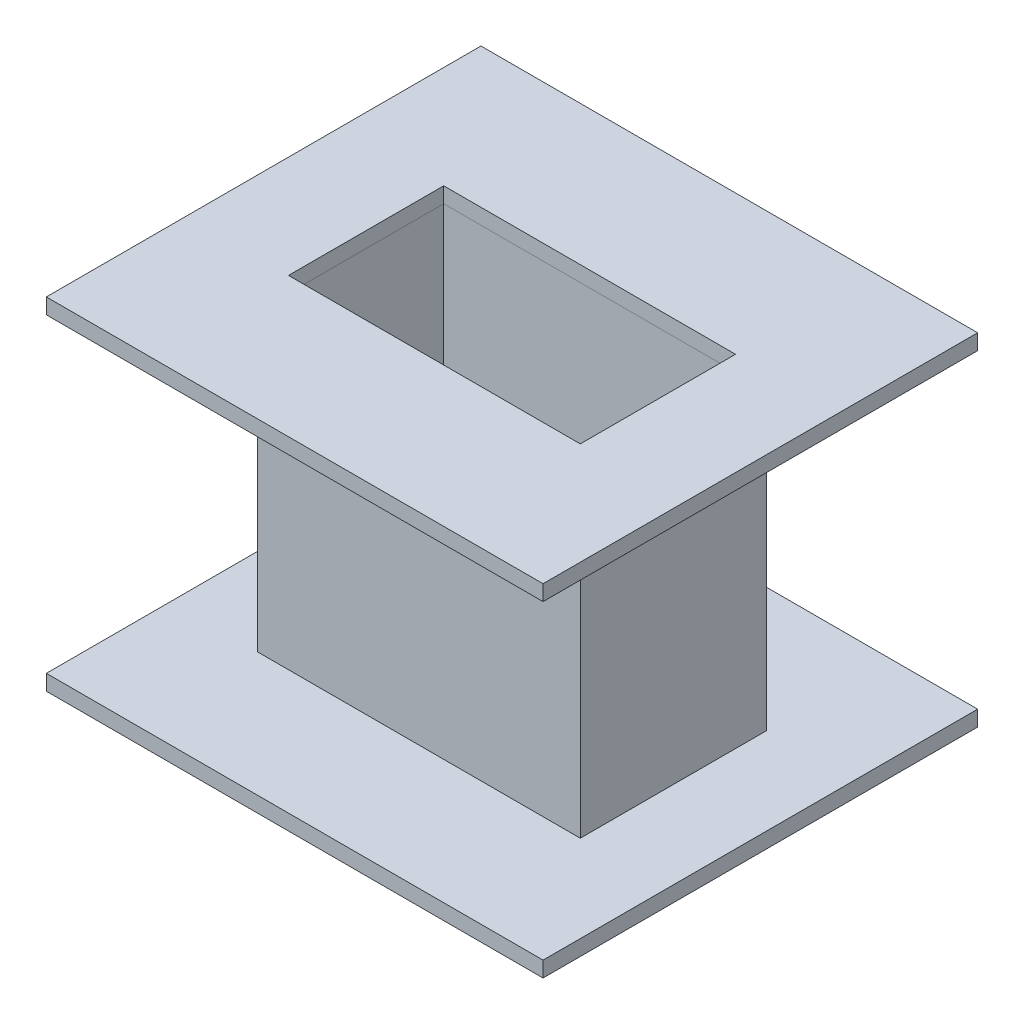
SolidWorks part; units mm, degrees
ref_plane "Front Plane" through (0, 0, 0) normal (0, 0, 1) x (1, 0, 0)
ref_plane "Top Plane" through (0, 0, 0) normal (0, 1, 0) x (1, 0, 0)
ref_plane "Right Plane" through (0, 0, 0) normal (1, 0, 0) x (0, 0, -1)
sketch "Sketch1" plane through (0, 0, 0) normal (0, 1, 0) x (1, 0, 0)
  line L0 (-26, 15) -> (-26, -15)
  line L1 (-23.5, 12.5) -> (23.5, 12.5)
  line L2 (-23.5, 12.5) -> (-23.5, -12.5)
  line L3 (-23.5, -12.5) -> (23.5, -12.5)
  line L4 (23.5, 12.5) -> (23.5, -12.5)
  line L5 (-23.5, 12.5) -> (23.5, -12.5) construction
  line L6 (-23.5, -12.5) -> (23.5, 12.5) construction
  line L7 (-26, -15) -> (26, -15)
  line L8 (26, 15) -> (26, -15)
  line L9 (-26, 15) -> (26, 15)
  point P0 (0, 0)
  dimension "D1" = 25
  dimension "D2" = 47
  dimension "D4" = 2.5
  dimension "D3" = 2.5
extrude "Boss-Extrude1" add sketch "Sketch1" along normal mid plane 50
sketch "Sketch2" plane through (0, 25, 0) normal (0, 1, 0) x (1, 0, 0)
  line L20 (-40, 35) -> (40, 35)
  line L21 (-40, 35) -> (-40, -35)
  line L22 (-40, -35) -> (40, -35)
  line L23 (40, 35) -> (40, -35)
  line L24 (-40, 35) -> (40, -35) construction
  line L25 (-40, -35) -> (40, 35) construction
  point P0 (0, 0)
  point P1 (0, 0)
  point P7 (0, 0)
  point P9 (0, 0)
  point P14 (0, 0)
  dimension "D2" = 70
  dimension "D3" = 80
extrude "Boss-Extrude2" add sketch "Sketch2" along normal blind 2.5 separate body
mirror "Mirror2" about plane through (0, 0, 0) normal (0, 1, 0) of "Boss-Extrude2"
sketch "Sketch3" plane through (0, 27.5, 0) normal (0, 1, 0) x (1, 0, 0)
  line L1 (23.5, -12.5) -> (-23.5, -12.5)
  line L2 (23.5, -12.5) -> (23.5, 12.5)
  line L3 (23.5, 12.5) -> (-23.5, 12.5)
  line L4 (-23.5, -12.5) -> (-23.5, 12.5)
  line L5 (23.5, -12.5) -> (-23.5, 12.5) construction
  line L6 (23.5, 12.5) -> (-23.5, -12.5) construction
  point P0 (0, 0)
  dimension "D1" = 47
  dimension "D2" = 25
extrude "Cut-Extrude2" cut sketch "Sketch3" against normal blind 90
